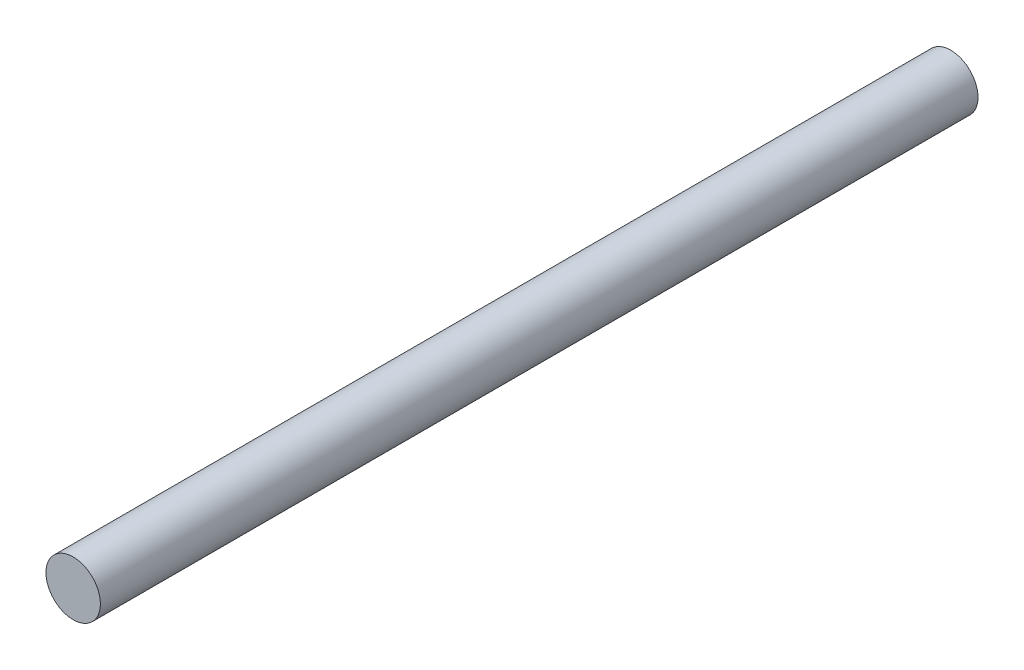
SolidWorks part; units mm, degrees
ref_plane "Front Plane" through (0, 0, 0) normal (0, 0, 1) x (1, 0, 0)
ref_plane "Top Plane" through (0, 0, 0) normal (0, 1, 0) x (1, 0, 0)
ref_plane "Right Plane" through (0, 0, 0) normal (1, 0, 0) x (0, 0, -1)
sketch "S01 - Steel rod and nominal threaded ends" plane through (0, 0, 0) normal (0, 0, 1) x (1, 0, 0)
  circle A0 centre (0, 0) radius 1.5
  dimension "D1" = 3
extrude "01 - Steel rod and nominal threaded ends" add sketch "S01 - Steel rod and nominal threaded ends" along normal blind 48.3649
